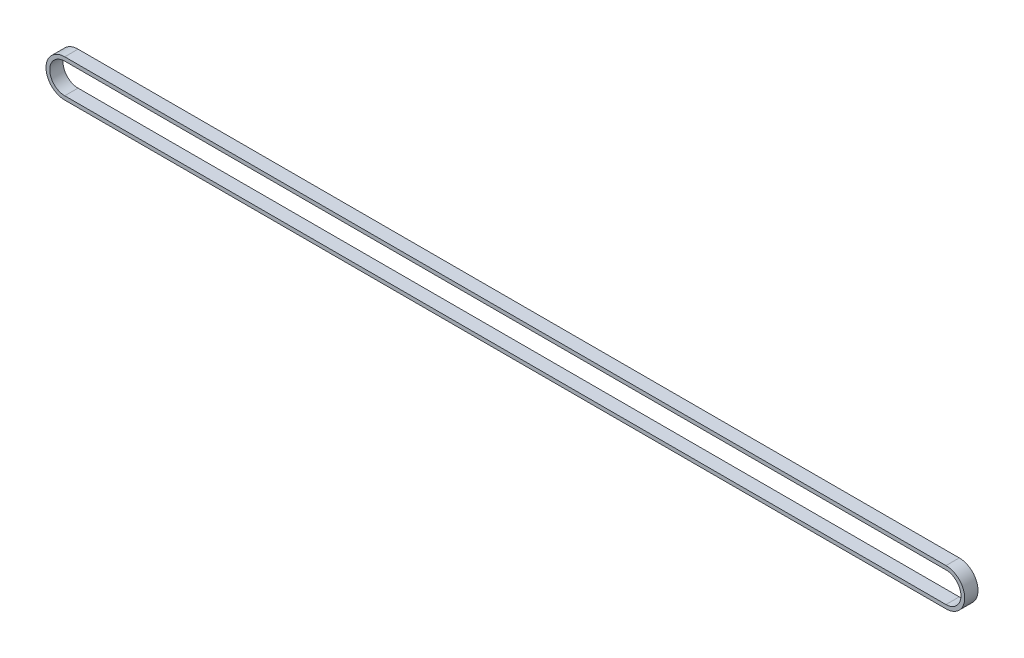
SolidWorks part; units mm, degrees
ref_plane "Front Plane" through (0, 0, 0) normal (0, 0, 1) x (1, 0, 0)
ref_plane "Top Plane" through (0, 0, 0) normal (0, 1, 0) x (1, 0, 0)
ref_plane "Right Plane" through (0, 0, 0) normal (1, 0, 0) x (0, 0, -1)
sketch "Sketch1" plane through (0, 0, 0) normal (0, 0, 1) x (1, 0, 0)
  line L0 (-298.45, 0) -> (298.45, 0) construction
  line L1 (-298.45, 10.16) -> (298.45, 10.16)
  line L2 (-298.45, -10.16) -> (298.45, -10.16)
  arc A0 (-298.45, 10.16) -> (-298.45, -10.16) centre (-298.45, 0) ccw
  arc A1 (298.45, -10.16) -> (298.45, 10.16) centre (298.45, 0) ccw
  point P3 (0, 0)
  dimension "D1" = 10.16
  dimension "D2" = 596.9
extrude "Extrude-Thin1" add sketch "Sketch1" along normal mid plane 9 thin thin type one direction wall 2.54
